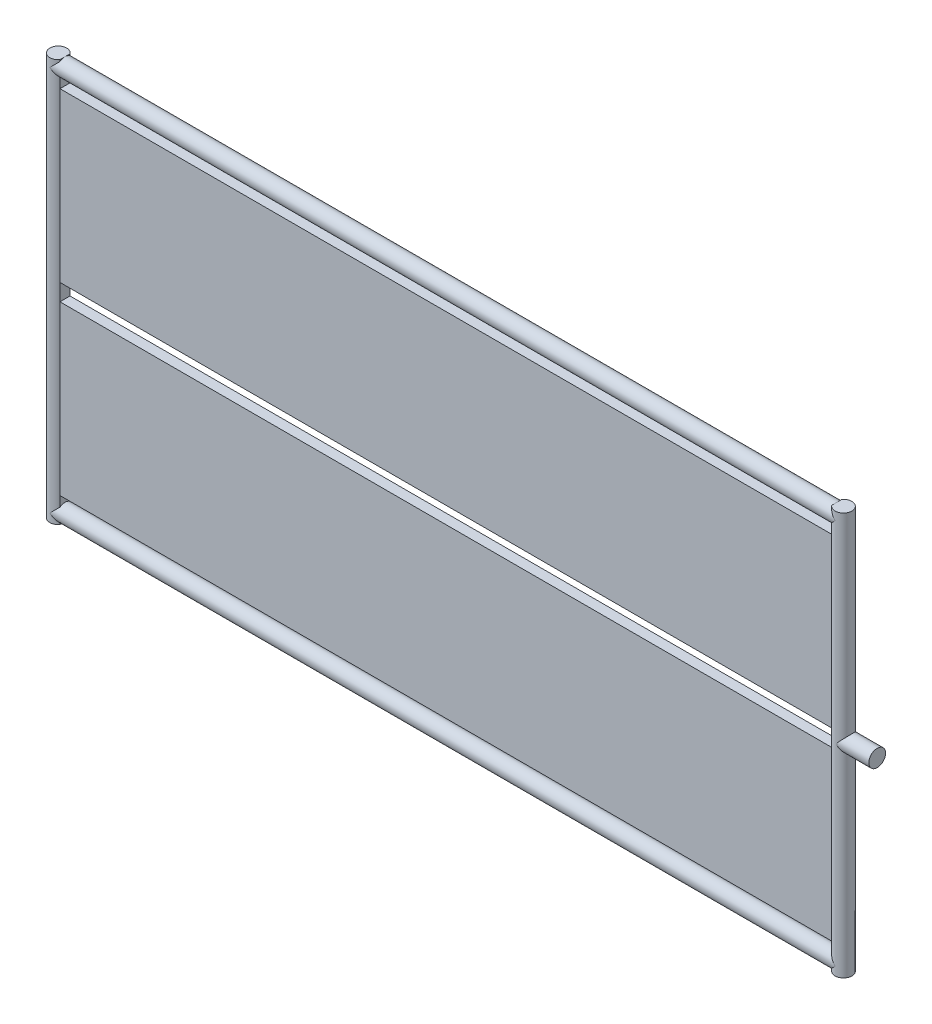
SolidWorks part; units mm, degrees
ref_plane "Front Plane" through (0, 0, 0) normal (0, 0, 1) x (1, 0, 0)
ref_plane "Top Plane" through (0, 0, 0) normal (0, 1, 0) x (1, 0, 0)
ref_plane "Right Plane" through (0, 0, 0) normal (1, 0, 0) x (0, 0, -1)
sketch "Sketch1" plane through (0, 0, 0) normal (0, 0, 1) x (1, 0, 0)
  line L0 (-1236.422, 0) -> (1503.093, 0) construction
  line L1 (-11500, 250) -> (11500, 250)
  line L2 (-11500, 250) -> (-11500, 5250)
  line L3 (-11500, 5250) -> (11500, 5250)
  line L4 (11500, 250) -> (11500, 5250)
  line L5 (-11500, 250) -> (11500, 5250) construction
  line L6 (-11500, 5250) -> (11500, 250) construction
  line L7 (-11500, -5250) -> (11500, -5250)
  line L8 (11500, -250) -> (11500, -5250)
  line L9 (-11500, -250) -> (11500, -250)
  line L10 (-11500, -250) -> (-11500, -5250)
  point P0 (0, 5250)
  dimension "D1" = 23000
  dimension "D2" = 5000
  dimension "D3" = 250
extrude "Boss-Extrude1" add sketch "Sketch1" along normal blind 300
sketch "Sketch2" plane through (0, 0, 0) normal (0, 1, 0) x (1, 0, 0)
  line L0 (-11500, 0) -> (-11500, -300)
  line L1 (-11500, -300) -> (-11500, 0) construction
  line L2 (11500, 0) -> (-11500, 0) construction
  line L3 (0, -55) -> (0, 55) construction
  line L4 (11500, 0) -> (11500, -300)
  arc A0 (-11500, 0) -> (-11500, -300) centre (-11700, -150) ccw
  arc A1 (11500, 0) -> (11500, -300) centre (11700, -150) cw
  point P5 (0, 0)
  point P6 (0, 0)
  dimension "D1" = 500
  dimension "D2" = 300
extrude "Boss-Extrude2" add sketch "Sketch2" along normal blind 6000 and the other way blind 6000 contours A1 L4 | A0 L0
sketch "Sketch4" plane through (-11500, 0, 0) normal (1, 0, 0) x (0, 0, -1)
  line L1 (0, 6000) -> (-300, 6000) construction
  line L3 (55, 0) -> (-55, 0) construction
  circle A0 centre (-150, 5750) radius 250
  circle A1 centre (-150, -5750) radius 250
  point P4 (0, 0)
  point P5 (-150, 6000)
  point P6 (0, 0)
  point P7 (0, 0)
  point P8 (-141.215, 5945.3244)
  point P9 (-150, 6000)
  dimension "D1" = 500
extrude "Boss-Extrude3" add sketch "Sketch4" along normal blind 23194.882 and the other way blind 199.962
sketch "Sketch5" plane through (11500, 0, 0) normal (-1, 0, 0) x (0, 0, 1)
  circle A0 centre (145.7645, 0) radius 250
  point P2 (0, 0)
  point P5 (0, 0)
  dimension "D1" = 500
extrude "Boss-Extrude4" add sketch "Sketch5" against normal blind 1000 from offset 199.962 offset against normal yes
